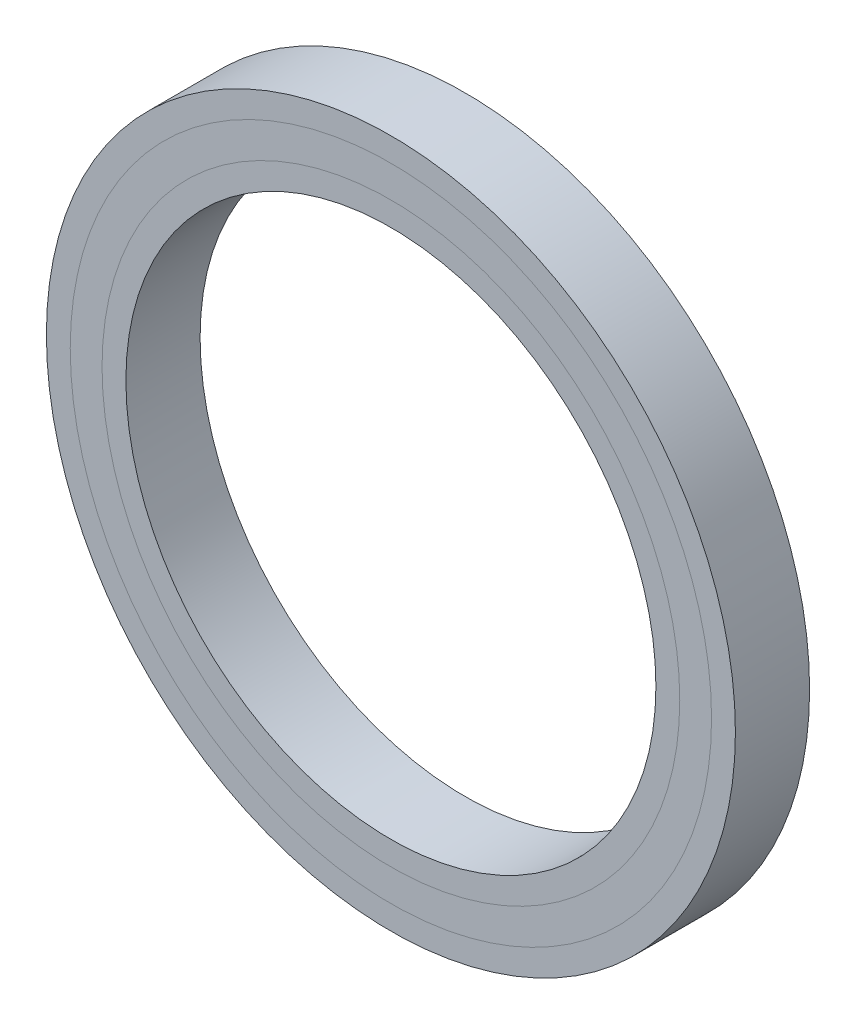
SolidWorks part; units mm, degrees
ref_plane "Front Plane" through (0, 0, 0) normal (0, 0, 1) x (1, 0, 0)
ref_plane "Top Plane" through (0, 0, 0) normal (0, 1, 0) x (1, 0, 0)
ref_plane "Right Plane" through (0, 0, 0) normal (1, 0, 0) x (0, 0, -1)
sketch "Sketch1" plane through (0, 0, 0) normal (0, 0, 1) x (1, 0, 0)
  circle A0 centre (0, 0) radius 25
  circle A1 centre (0, 0) radius 27.25
  dimension "D1" = 50
  dimension "D2" = 54.5
extrude "Boss-Extrude1" add sketch "Sketch1" along normal blind 7
sketch "Sketch3" plane through (0, 0, 0) normal (0, 0, 1) x (1, 0, 0)
  circle A0 centre (0, 0) radius 30.25
  circle A1 centre (0, 0) radius 27.25
  dimension "D1" = 60.5
  dimension "D2" = 54.5
extrude "Boss-Extrude4" add sketch "Sketch3" along normal blind 7 separate body
sketch "Sketch5" plane through (0, 0, 0) normal (0, 0, 1) x (1, 0, 0)
  circle A0 centre (0, 0) radius 30.25
  circle A1 centre (0, 0) radius 32.5
  dimension "D1" = 60.5
  dimension "D2" = 65
extrude "Boss-Extrude5" add sketch "Sketch5" along normal blind 7 separate body
